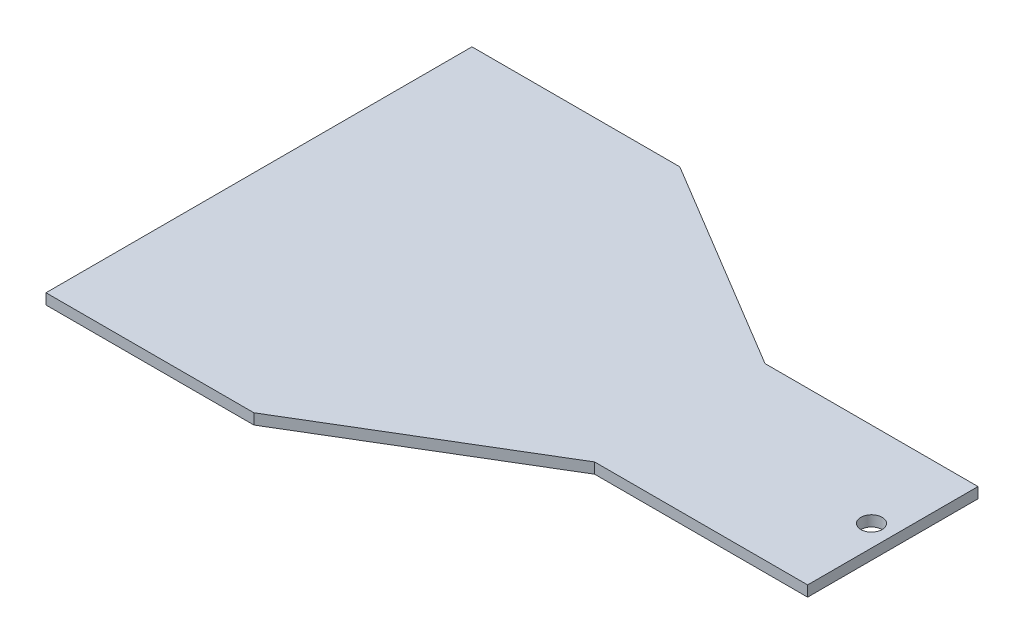
SolidWorks part; units mm, degrees
ref_plane "Front Plane" through (0, 0, 0) normal (0, 0, 1) x (1, 0, 0)
ref_plane "Top Plane" through (0, 0, 0) normal (0, 1, 0) x (1, 0, 0)
ref_plane "Right Plane" through (0, 0, 0) normal (1, 0, 0) x (0, 0, -1)
sketch "Sketch1" plane through (0, 0, 0) normal (0, 1, 0) x (1, 0, 0)
  line L0 (61.976, 0) -> (125.476, 38.1)
  line L1 (0, 0) -> (61.976, 0)
  line L2 (0, 0) -> (0, 127)
  line L3 (0, 127) -> (61.976, 127)
  line L5 (125.476, 38.1) -> (188.976, 38.1)
  line L7 (125.476, 88.9) -> (188.976, 88.9)
  line L8 (188.976, 38.1) -> (188.976, 88.9)
  line L10 (125.476, 88.9) -> (61.976, 127)
  circle A0 centre (182.626, 63.5) radius 3.175
  dimension "D6" = 6.35
  dimension "D8" = 25.4
  dimension "D1" = 127
  dimension "D2" = 61.976
  dimension "D3" = 50.8
  dimension "D4" = 38.1
  dimension "D7" = 6.35
extrude "Boss-Extrude1" add sketch "Sketch1" along normal blind 3.175
